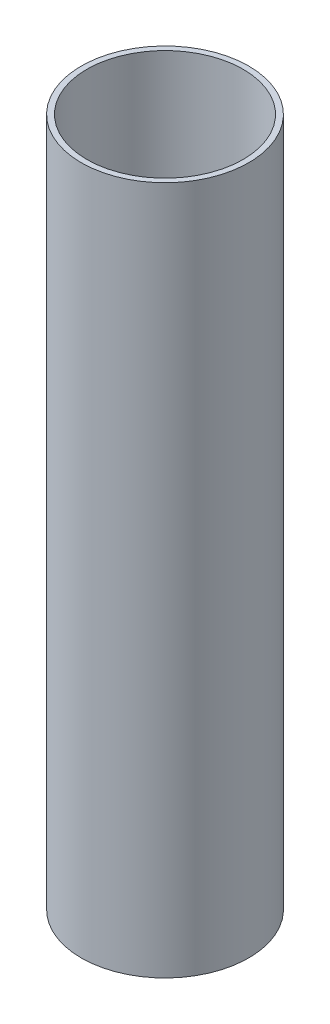
SolidWorks part; units mm, degrees
ref_plane "前视基准面" through (0, 0, 0) normal (0, 0, 1) x (1, 0, 0)
ref_plane "上视基准面" through (0, 0, 0) normal (0, 1, 0) x (1, 0, 0)
ref_plane "右视基准面" through (0, 0, 0) normal (1, 0, 0) x (0, 0, -1)
sketch "草图1" plane through (0, 0, 0) normal (0, 1, 0) x (1, 0, 0)
  circle A0 centre (0, 0) radius 21
  circle A1 centre (0, 0) radius 22.5
  dimension "D1" = 45
  dimension "D2" = 42
extrude "凸台-拉伸1" add sketch "草图1" along normal blind 185
